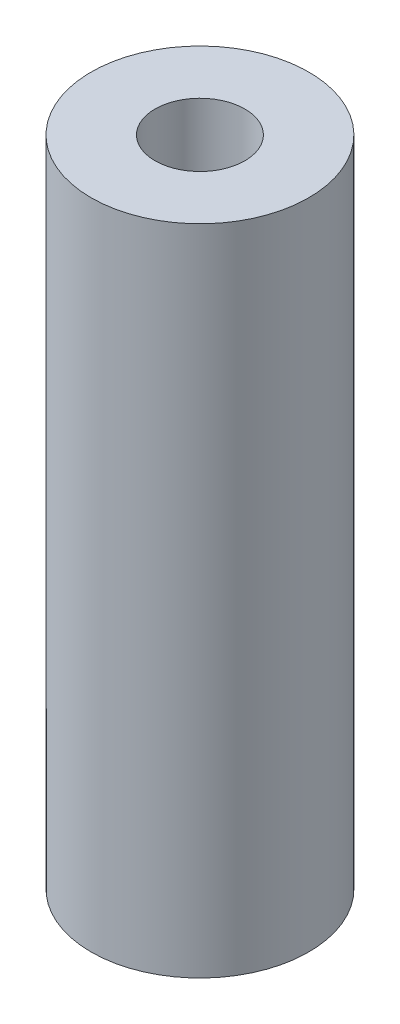
SolidWorks part; units mm, degrees
material "6061-T6 (SS)"
ref_plane "Front Plane" through (0, 0, 0) normal (0, 0, 1) x (1, 0, 0)
ref_plane "Top Plane" through (0, 0, 0) normal (0, 1, 0) x (1, 0, 0)
ref_plane "Right Plane" through (0, 0, 0) normal (1, 0, 0) x (0, 0, -1)
sketch "Sketch2" plane through (0, 0, 0) normal (0, 1, 0) x (1, 0, 0)
  circle A0 centre (0, 0) radius 4
  dimension "D1" = 8
extrude "Boss-Extrude1" add sketch "Sketch2" along normal blind 24
sketch "Sketch3" plane through (0, 24, 0) normal (0, 1, 0) x (1, 0, 0)
  circle A0 centre (0, 0) radius 1.65
  dimension "D1" = 3.3
extrude "Cut-Extrude1" cut sketch "Sketch3" against normal blind 8
sketch "Sketch4" plane through (0, 0, 0) normal (0, -1, 0) x (1, 0, 0)
  circle A0 centre (0, 0) radius 1.65
  dimension "D1" = 3.3
extrude "Cut-Extrude2" cut sketch "Sketch4" against normal blind 8
equation "\"____ GENERATED PART EXPORTS ____\" = 0"
equation "\"SYS_VersionTag\" = 2"
equation "\"UTR_OD\" = 8mm"
equation "\"UTR_StandoffLength\" = 24mm"
equation "\"D1@Sketch2\"=\"UTR_OD\""
equation "\"D1@Boss-Extrude1\"=\"UTR_StandoffLength\""
